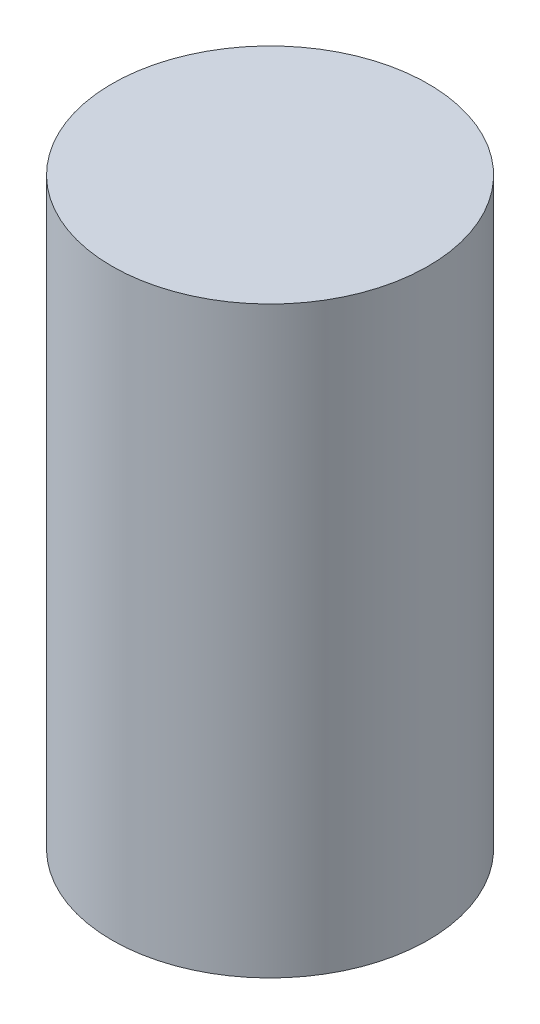
SolidWorks part; units mm, degrees
ref_plane "Front Plane" through (0, 0, 0) normal (0, 0, 1) x (1, 0, 0)
ref_plane "Top Plane" through (0, 0, 0) normal (0, 1, 0) x (1, 0, 0)
ref_plane "Right Plane" through (0, 0, 0) normal (1, 0, 0) x (0, 0, -1)
sketch "Sketch1" plane through (0, 0, 0) normal (0, 1, 0) x (1, 0, 0)
  circle A0 centre (0, 0) radius 32.5
  dimension "D1" = 65
extrude "Boss-Extrude1" add sketch "Sketch1" along normal blind 120
